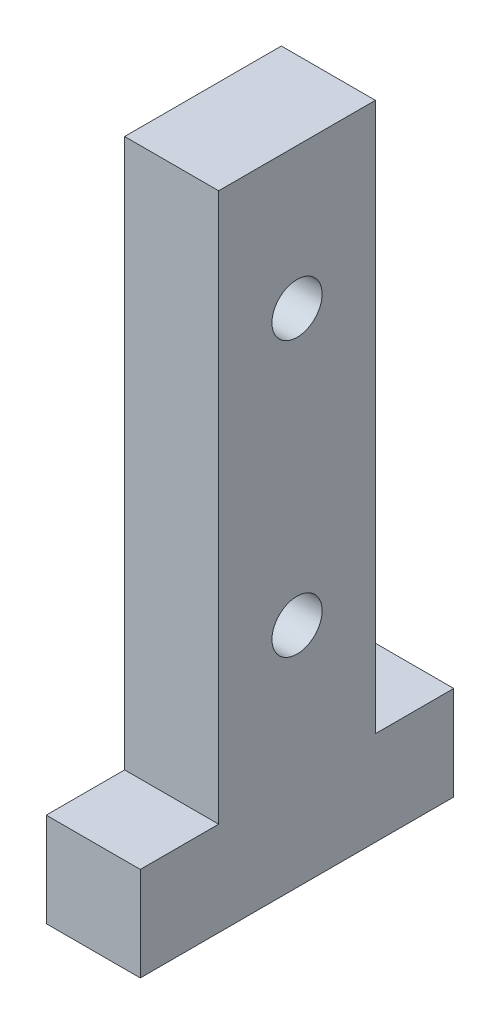
SolidWorks part; units mm, degrees
material "Oak"
ref_plane "Front Plane" through (0, 0, 0) normal (0, 0, 1) x (1, 0, 0)
ref_plane "Top Plane" through (0, 0, 0) normal (0, 1, 0) x (1, 0, 0)
ref_plane "Right Plane" through (0, 0, 0) normal (1, 0, 0) x (0, 0, -1)
sketch "Sketch1" plane through (0, 0, 0) normal (1, 0, 0) x (0, 0, -1)
  line L0 (5, 6) -> (10, 6)
  line L1 (-10, 0) -> (10, 0)
  line L2 (-10, 0) -> (-10, 6)
  line L3 (-10, 6) -> (-5, 6)
  line L4 (10, 0) -> (10, 6)
  line L6 (-5, 6) -> (-5, 41)
  line L7 (-5, 41) -> (5, 41)
  line L8 (5, 6) -> (5, 41)
  circle A0 centre (0, 32) radius 1.6
  circle A1 centre (0, 14.5) radius 1.6
  point P11 (0, 0)
  dimension "D5" = 3.2
  dimension "D7" = 8.5
  dimension "D8" = 17.5
  dimension "D1" = 10
  dimension "D2" = 20
  dimension "D3" = 6
  dimension "D4" = 35
  dimension "D6" = 2
extrude "Boss-Extrude1" add sketch "Sketch1" along normal blind 6
